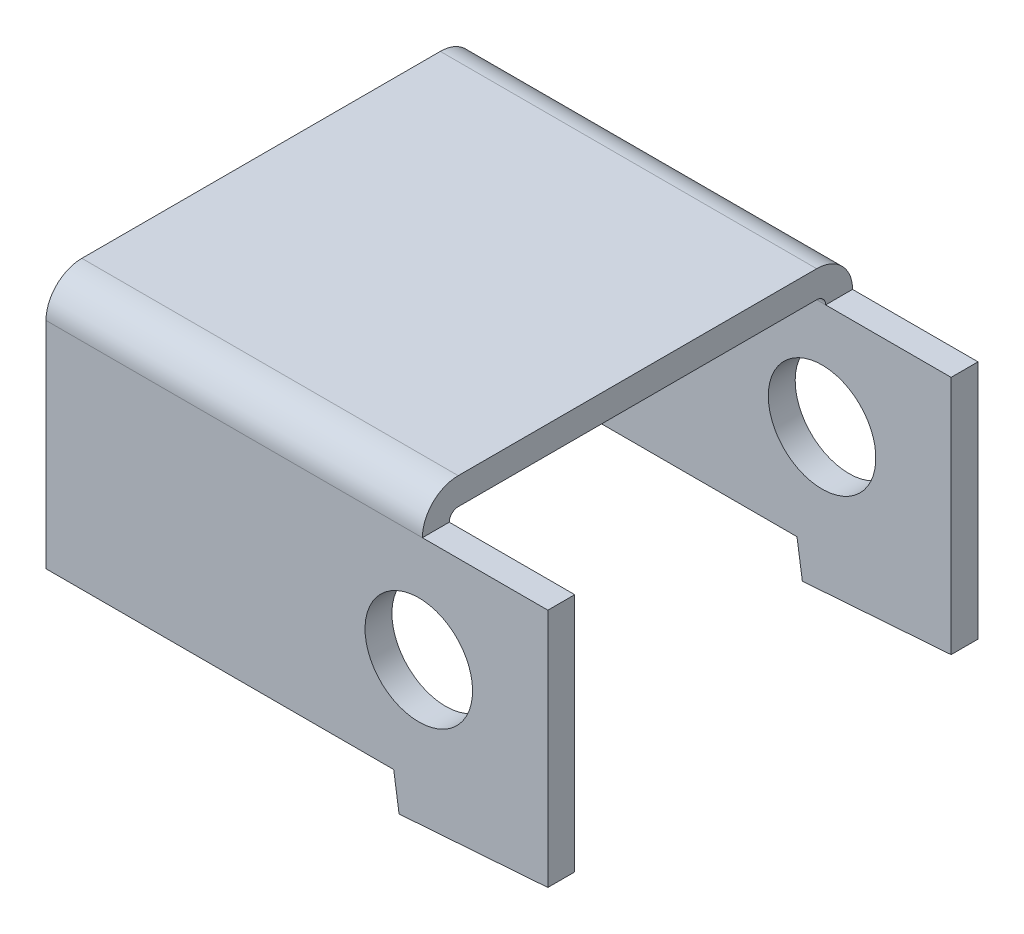
SolidWorks part; units mm, degrees
ref_plane "Front Plane" through (0, 0, 0) normal (0, 0, 1) x (1, 0, 0)
ref_plane "Top Plane" through (0, 0, 0) normal (0, 1, 0) x (1, 0, 0)
ref_plane "Right Plane" through (0, 0, 0) normal (1, 0, 0) x (0, 0, -1)
sketch "Sketch1" plane through (0, 0, 0) normal (0, 0, 1) x (1, 0, 0)
  line L0 (-10.4, -3) -> (-0.7, -3)
  line L2 (-10.4, -3) -> (-10.4, 4)
  line L3 (-10.4, 4) -> (3.6, 4)
  line L4 (3.6, -3.7) -> (3.6, 4)
  line L5 (-0.7, -3) -> (-0.55, -4)
  line L6 (-0.55, -4) -> (3.6, -3.7)
  circle A0 centre (0, 0) radius 1.5
  dimension "D3" = 3
  dimension "D1" = 14
  dimension "D2" = 8
  dimension "D4" = 1
  dimension "D5" = 4
  dimension "D6" = 0.15
  dimension "D7" = 3.6
  dimension "D8" = 0.3
  dimension "D9" = 9.85
extrude "Boss-Extrude1" add sketch "Sketch1" along normal mid plane 12
fillet "Fillet1" radius 1 2 edges at (-3.4, 4, -6) (-3.4, 4, 6)
sketch "Sketch2" plane through (0, 0, 0) normal (1, 0, 0) x (0, 0, -1)
  line L1 (-5.25, 3) -> (-5.25, -4)
  line L2 (5, 3.25) -> (-5, 3.25)
  line L3 (5, 3.25) -> (-5, 3.25)
  line L4 (-6, -4) -> (6, -4) construction
  line L5 (-5.25, -4) -> (5.25, -4)
  line L6 (5.25, -4) -> (5.25, 3)
  arc A4 (5.25, 3) -> (5, 3.25) centre (5, 3) ccw
  arc A5 (-5, 3.25) -> (-5.25, 3) centre (-5, 3) ccw
  arc A6 (5.25, 3) -> (5, 3.25) centre (5, 3) ccw
  arc A7 (-5, 3.25) -> (-5.25, 3) centre (-5, 3) ccw
  dimension "D1" = 0.75
extrude "Cut-Extrude2" cut sketch "Sketch2" against normal through all both and the other way through all
sketch "Sketch3" plane through (3.6, 0, 0) normal (1, 0, 0) x (0, 0, -1)
  line L0 (-5, 4) -> (5, 4) construction
  line L1 (-5, 4) -> (5, 4)
  line L2 (-6, 3) -> (6, 3)
  arc A0 (6, 3) -> (5, 4) centre (5, 3) ccw construction
  arc A1 (-5, 4) -> (-6, 3) centre (-5, 3) ccw construction
  arc A2 (6, 3) -> (5, 4) centre (5, 3) ccw
  arc A3 (-5, 4) -> (-6, 3) centre (-5, 3) ccw
extrude "Cut-Extrude3" cut sketch "Sketch3" against normal blind 3.5 and the other way through all
